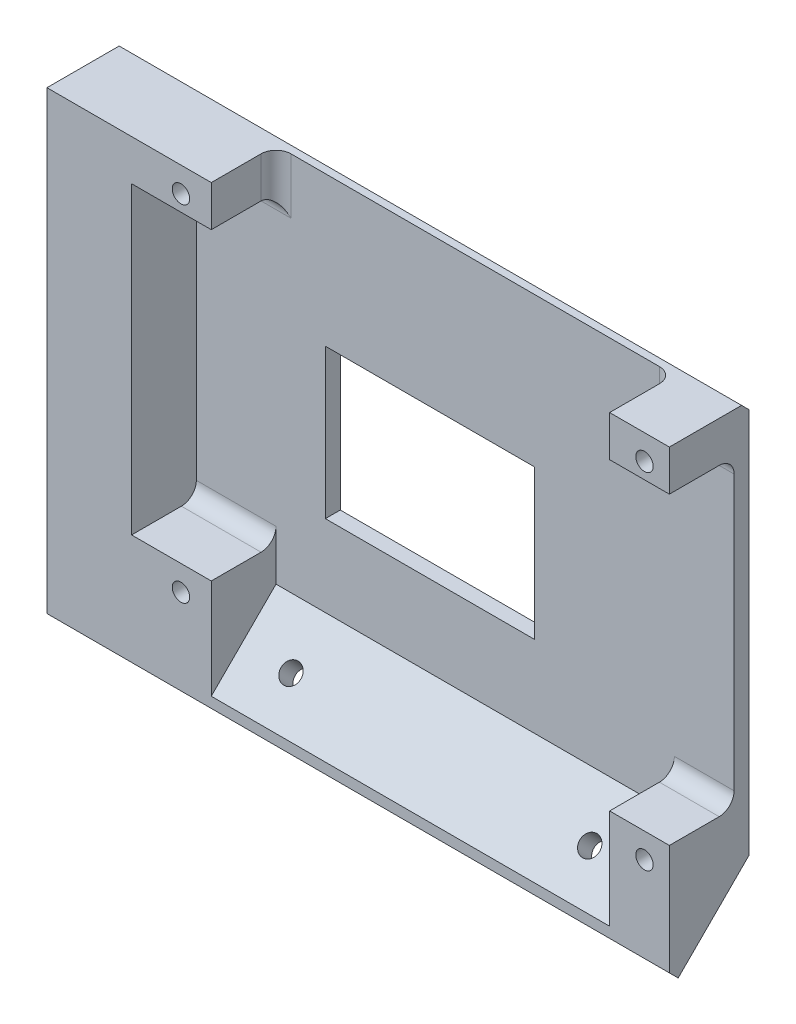
SolidWorks part; units mm, degrees
ref_plane "前视基准面" through (0, 0, 0) normal (0, 0, 1) x (1, 0, 0)
ref_plane "上视基准面" through (0, 0, 0) normal (0, 1, 0) x (1, 0, 0)
ref_plane "右视基准面" through (0, 0, 0) normal (1, 0, 0) x (0, 0, -1)
sketch "草图1" plane through (0, 0, 0) normal (0, 0, 1) x (1, 0, 0)
  line L1 (0, 0) -> (125, 0)
  line L2 (0, 0) -> (0, 95)
  line L3 (0, 95) -> (125, 95)
  line L4 (125, 0) -> (125, 95)
  dimension "D1" = 125
  dimension "D2" = 95
extrude "凸台-拉伸1" add sketch "草图1" along normal blind 16
sketch "草图3" plane through (0, 0, 16) normal (0, 0, 1) x (1, 0, 0)
  line L0 (125, 0) -> (125, 95) construction
  line L2 (125, 95) -> (0, 95) construction
  circle A0 centre (26.91, 90) radius 1.75
  circle A1 centre (26.91, 20.71) radius 1.75
  circle A2 centre (120, 90) radius 1.75
  circle A3 centre (120, 20.71) radius 1.75
  dimension "D1" = 3.5
  dimension "D2" = 3.5
  dimension "D3" = 3.5
  dimension "D4" = 3.5
  dimension "D5" = 93.09
  dimension "D6" = 69.29
  dimension "D7" = 5
  dimension "D8" = 5
extrude "切除-拉伸1" cut sketch "草图3" against normal through all
sketch "草图4" plane through (0, 0, 16) normal (0, 0, 1) x (1, 0, 0)
  line L1 (33, 95) -> (33, 86.8)
  line L2 (125, 95) -> (0, 95) construction
  line L3 (33, 86.8) -> (17, 86.8)
  line L4 (17, 86.8) -> (17, 25.71)
  line L6 (17, 25.71) -> (33, 25.71)
  line L7 (33, 25.71) -> (33, 0)
  line L8 (0, 0) -> (125, 0) construction
  line L9 (33, 0) -> (113, 0)
  line L10 (113, 0) -> (113, 25.71)
  line L11 (113, 25.71) -> (125, 25.71)
  line L12 (125, 0) -> (125, 95) construction
  line L13 (125, 25.71) -> (125, 86.8)
  line L14 (125, 86.8) -> (113, 86.8)
  line L15 (113, 86.8) -> (113, 95)
  line L16 (113, 95) -> (33, 95)
  circle A0 centre (120, 20.71) radius 1.75 construction
  circle A1 centre (26.91, 90) radius 1.75 construction
  dimension "D1" = 5
  dimension "D2" = 12
  dimension "D3" = 80
  dimension "D4" = 16
  dimension "D5" = 3.2
extrude "切除-拉伸2" cut sketch "草图4" against normal blind 13
sketch "草图5" plane through (125, 0, 0) normal (1, 0, 0) x (0, 0, -1)
  line L0 (-16, 0) -> (0, 16)
  line L1 (0, 0) -> (0, 95) construction
  line L2 (0, 16) -> (0, 0)
  line L3 (0, 0) -> (-16, 0)
  dimension "D1" = 16
extrude "切除-拉伸3" cut sketch "草图5" against normal through all
sketch "草图8" plane through (33, 0, 0) normal (1, 0, 0) x (0, 0, -1)
  line L0 (-16, 0) -> (-3, 13)
  line L1 (-16, 25.71) -> (-16, 0) construction
  line L2 (-16, 0) -> (-3, 13) construction
  line L3 (-3, 13) -> (-3, 18.6569)
  line L4 (-3, 25.71) -> (-3, 13) construction
  line L5 (-3, 18.6569) -> (-16, 5.6569)
  line L6 (-16, 5.6569) -> (-16, 0)
  dimension "D1" = 4
extrude "凸台-拉伸4" add sketch "草图8" along normal blind 80
hole_wizard "Ø4.0 (4) 直径孔1" positions "草图10" profile "草图9" hole size "Ø4.0" standard "GB" end condition through all
sketch "草图10" plane through (0, 10.8284, 10.8284) normal (0, 0.7071, 0.7071) x (1, 0, 0)
  line L0 (113, 11.0711) -> (113, -7.3137) construction
  line L1 (0, -11.3137) -> (125, -11.3137) construction
  point P0 (43, 1.1863)
  point P2 (103, 1.1863)
  dimension "D1" = 60
  dimension "D2" = 10
  dimension "D3" = 12.5
sketch "草图9" plane through (43, 11.6673, 9.9896) normal (1, 0, 0) x (0, -0.7071, 0.7071)
  line L0 (0, 0) -> (0, 15.3137)
  line L1 (0, 15.3137) -> (2, 15.3137)
  line L2 (2, 15.3137) -> (2, 0)
  line L5 (2, 0) -> (0, 0)
  line L11 (0, -6.35) -> (0, 107.95) construction
  dimension "通孔孔直径" = 4
  dimension "通孔孔深度" = 15.3137
sketch "草图11" plane through (0, 0, 3) normal (0, 0, 1) x (1, 0, 0)
  line L1 (42.91, 35) -> (84.91, 35)
  line L2 (42.91, 35) -> (42.91, 65)
  line L3 (42.91, 65) -> (84.91, 65)
  line L4 (84.91, 35) -> (84.91, 65)
  circle A0 centre (26.91, 90) radius 1.75 construction
  dimension "D3" = 25
  dimension "D1" = 42
  dimension "D2" = 30
  dimension "D4" = 16
extrude "切除-拉伸4" cut sketch "草图11" against normal through all
fillet "圆角4" radius 3 6 edges at (25, 86.8, 3) (113, 90.9, 3) (119, 86.8, 3) (119, 25.71, 3) (25, 25.71, 3) (33, 90.9, 3)
chamfer "倒角1" distance 2.5 angle 90 1 edges at (62.5, 0, 16)
hole_wizard "Ø2.5 (2.5) 直径孔1" positions "草图15" profile "草图14" hole size "Ø2.5" standard "GB"
sketch "草图15" plane through (0, 0, 0) normal (-1, 0, 0) x (0, 0, 1)
  line L0 (16, 95) -> (16, 3.5355) construction
  line L1 (16, 95) -> (0, 95) construction
  point P0 (8, 83)
  point P2 (8, 53)
  point P4 (8, 23)
  dimension "D1" = 30
  dimension "D2" = 30
  dimension "D3" = 8
  dimension "D4" = 12
sketch "草图14" plane through (0, 83, 8) normal (0, 1, 0) x (0, 0, 1)
  line L0 (0, 0) -> (0, 16.7511)
  line L1 (0, 16.7511) -> (1.25, 16)
  line L2 (1.25, 16) -> (1.25, 0)
  line L5 (1.25, 0) -> (0, 0)
  line L10 (0, 16.7511) -> (-1.25, 16) construction
  line L11 (0, -6.35) -> (0, 107.95) construction
  dimension "孔直径" = 2.5
  dimension "孔深度" = 16
  dimension "导头角度" = 118
chamfer "倒角2" distance 1.5 angle 45 1 edges at (62.5, 95, 0)
